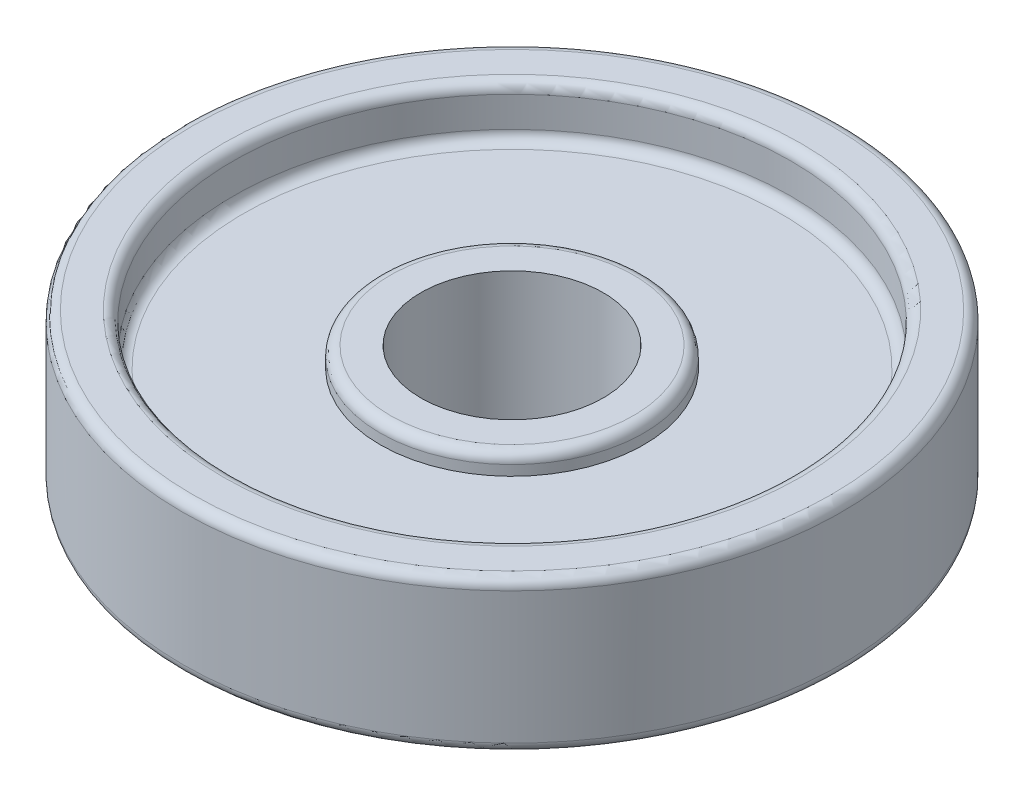
SolidWorks part; units mm, degrees
ref_plane "Front Plane" through (0, 0, 0) normal (0, 0, 1) x (1, 0, 0)
ref_plane "Top Plane" through (0, 0, 0) normal (0, 1, 0) x (1, 0, 0)
ref_plane "Right Plane" through (0, 0, 0) normal (1, 0, 0) x (0, 0, -1)
sketch "Sketch1" plane through (0, 0, 0) normal (0, 0, 1) x (1, 0, 0)
  line L0 (0, 19) -> (0, 0) construction
  line L1 (0, 0) -> (-26.7407, 0) construction
  line L2 (-9, 16) -> (-13, 16)
  line L3 (-13, 16) -> (-13, 14)
  line L4 (-13, 14) -> (-27.5, 14)
  line L5 (-27.5, 14) -> (-27.5, 19)
  line L6 (-27.5, 19) -> (-32.5, 19)
  line L7 (-32.5, 19) -> (-32.5, 4)
  line L10 (-32.5, 4) -> (-27.5, 4)
  line L11 (-27.5, 4) -> (-27.5, 9)
  line L12 (-27.5, 9) -> (-13, 9)
  line L13 (-13, 9) -> (-13, 0)
  line L14 (-13, 0) -> (-9, 0)
  line L15 (-9, 0) -> (-9, 16)
  line L16 (-32.5, 11.5) -> (-21.0932, 11.5) construction
  point P17 (-27.5, 6.5)
  dimension "D1" = 19
  dimension "D2" = 16
  dimension "D3" = 9
  dimension "D4" = 15
  dimension "D5" = 5
  dimension "D6" = 4
  dimension "D7" = 9
  dimension "D8" = 14.5
revolve "Revolve1" add sketch "Sketch1" angle 360 about L0
fillet "Fillet1" radius 1 8 edges at (0, 0, 13) (0, 9, 27.5) (0, 16, 13) (0, 14, 27.5) (0, 19, 27.5) (0, 19, 32.5) (0, 4, 32.5) (0, 4, 27.5)
